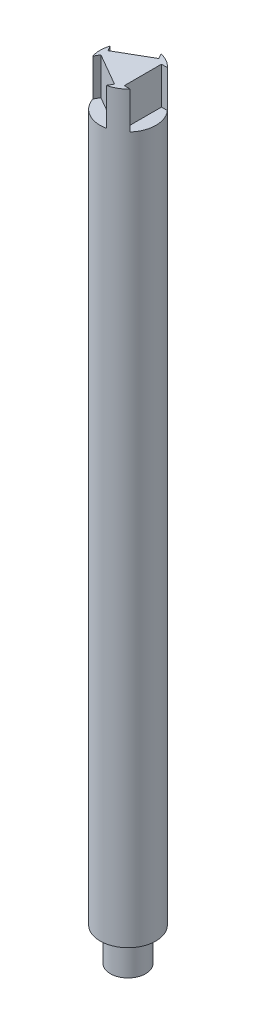
SolidWorks part; units mm, degrees
ref_plane "Front Plane" through (0, 0, 0) normal (0, 0, 1) x (1, 0, 0)
ref_plane "Top Plane" through (0, 0, 0) normal (0, 1, 0) x (1, 0, 0)
ref_plane "Right Plane" through (0, 0, 0) normal (1, 0, 0) x (0, 0, -1)
sketch "Sketch1" plane through (0, 0, 0) normal (0, 1, 0) x (1, 0, 0)
  circle A0 centre (0, 0) radius 4.75
  dimension "D1" = 9.5
extrude "Boss-Extrude1" add sketch "Sketch1" along normal blind 9
sketch "Sketch2" plane through (0, 9, 0) normal (0, 1, 0) x (1, 0, 0)
  circle A0 centre (0, 0) radius 7.5
  dimension "D1" = 15
extrude "Boss-Extrude2" add sketch "Sketch2" along normal blind 200
sketch "Sketch3" plane through (0, 0, 0) normal (1, 0, 0) x (0, 0, -1)
  line L0 (7.5, 209) -> (-7.5, 209) construction
  line L1 (-5, 199) -> (5, 199)
  line L2 (-5, 199) -> (-5, 209)
  line L3 (-5, 209) -> (5, 209)
  line L4 (5, 199) -> (5, 209)
  line L5 (-5, 199) -> (5, 209) construction
  line L6 (-5, 209) -> (5, 199) construction
  point P0 (0, 204)
  point P7 (0, 0)
  dimension "D1" = 10
  dimension "D2" = 10
extrude "Cut-Extrude1" cut sketch "Sketch3" along normal through all from offset 4
pattern_circular "CirPattern2" count 3 over 360 about axis through (0, 0, 0) along (0, 1, 0) of "Cut-Extrude1"
